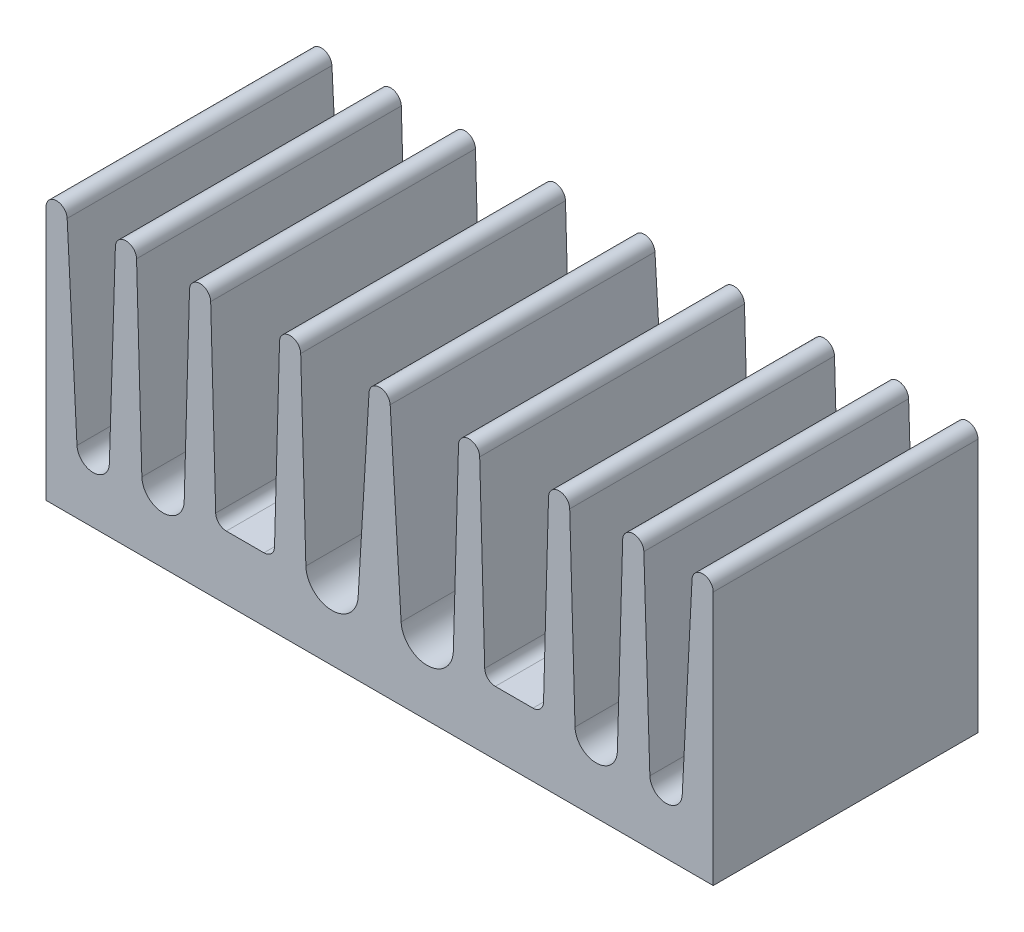
SolidWorks part; units mm, degrees
material "Alliage 2018"
ref_plane "Plan de face" through (0, 0, 0) normal (0, 0, 1) x (1, 0, 0)
ref_plane "Plan de dessus" through (0, 0, 0) normal (0, 1, 0) x (1, 0, 0)
ref_plane "Plan de droite" through (0, 0, 0) normal (1, 0, 0) x (0, 0, -1)
sketch "Esquisse1" plane through (0, 0, 0) normal (0, 0, 1) x (1, 0, 0)
  line L63 (20.5725, 7.9005) -> (17.0178, 7.9005)
  line L64 (16.0182, 8.8728) -> (15.5448, 25.9283)
  line L65 (13.5456, 25.929) -> (13.0573, 8.8001)
  line L66 (8.1227, 8.7233) -> (7.0934, 25.9626)
  line L67 (5.0969, 25.9626) -> (4.0675, 8.7233)
  line L68 (-0.8671, 8.8001) -> (-1.3553, 25.929)
  line L69 (-3.3545, 25.9283) -> (-3.8279, 8.8728)
  line L70 (-4.8275, 7.9005) -> (-8.3822, 7.9005)
  line L71 (-9.3818, 8.8728) -> (-9.8552, 25.9283)
  line L72 (-11.8544, 25.929) -> (-12.3557, 8.3435)
  line L73 (-16.354, 8.3435) -> (-16.8553, 25.929)
  line L74 (-18.8544, 25.9319) -> (-19.422, 7.8824)
  line L75 (-22.4792, 7.8523) -> (-23.4062, 25.9517)
  line L76 (-25.4049, 25.9005) -> (-25.4049, 1.9005)
  line L77 (-25.4049, 1.9005) -> (37.5951, 1.9005)
  line L78 (37.5951, 1.9005) -> (37.5951, 25.9005)
  line L79 (35.5965, 25.9517) -> (34.6695, 7.8523)
  line L80 (31.6123, 7.8824) -> (31.0447, 25.9319)
  line L81 (29.0456, 25.929) -> (28.5443, 8.3435)
  line L82 (24.546, 8.3435) -> (24.0447, 25.929)
  line L83 (22.0455, 25.9283) -> (21.5721, 8.8728)
  arc A57 (16.0182, 8.8728) -> (17.0178, 7.9005) centre (17.0178, 8.9005) ccw
  arc A58 (15.5448, 25.9283) -> (13.5456, 25.929) centre (14.5451, 25.9005) ccw
  arc A59 (8.1227, 8.7233) -> (13.0573, 8.8001) centre (10.5883, 8.8705) ccw
  arc A60 (7.0934, 25.9626) -> (5.0969, 25.9626) centre (6.0951, 25.903) ccw
  arc A61 (-0.8671, 8.8001) -> (4.0675, 8.7233) centre (1.6019, 8.8705) ccw
  arc A62 (-1.3553, 25.929) -> (-3.3545, 25.9283) centre (-2.3549, 25.9005) ccw
  arc A63 (-4.8275, 7.9005) -> (-3.8279, 8.8728) centre (-4.8275, 8.9005) ccw
  arc A64 (-9.3818, 8.8728) -> (-8.3822, 7.9005) centre (-8.3822, 8.9005) ccw
  arc A65 (-9.8552, 25.9283) -> (-11.8544, 25.929) centre (-10.8549, 25.9005) ccw
  arc A66 (-16.354, 8.3435) -> (-12.3557, 8.3435) centre (-14.3549, 8.4005) ccw
  arc A67 (-16.8553, 25.929) -> (-18.8544, 25.9319) centre (-17.8549, 25.9005) ccw
  arc A68 (-22.4792, 7.8523) -> (-19.422, 7.8824) centre (-20.9512, 7.9305) ccw
  arc A69 (-23.4062, 25.9517) -> (-25.4049, 25.9005) centre (-24.4049, 25.9005) ccw
  arc A70 (37.5951, 25.9005) -> (35.5965, 25.9517) centre (36.5951, 25.9005) ccw
  arc A71 (31.6123, 7.8824) -> (34.6695, 7.8523) centre (33.1415, 7.9305) ccw
  arc A72 (31.0447, 25.9319) -> (29.0456, 25.929) centre (30.0451, 25.9005) ccw
  arc A73 (24.546, 8.3435) -> (28.5443, 8.3435) centre (26.5451, 8.4005) ccw
  arc A74 (24.0447, 25.929) -> (22.0455, 25.9283) centre (23.0451, 25.9005) ccw
  arc A75 (20.5725, 7.9005) -> (21.5721, 8.8728) centre (20.5725, 8.9005) ccw
extrude "Boss.-Extru.1" add sketch "Esquisse1" along normal blind 25 contours L77 L78 A70 L79 A71 L80 A72 L81 A73 L82 A74 L83 A75 L63 A57 L64 A58 L65 A59 L66 A60 L67 A61 L68 A62 L69 A63 L70 A64 L71 A65 L72 A66 L73 A67 L74 A68 L75 A69 L76
